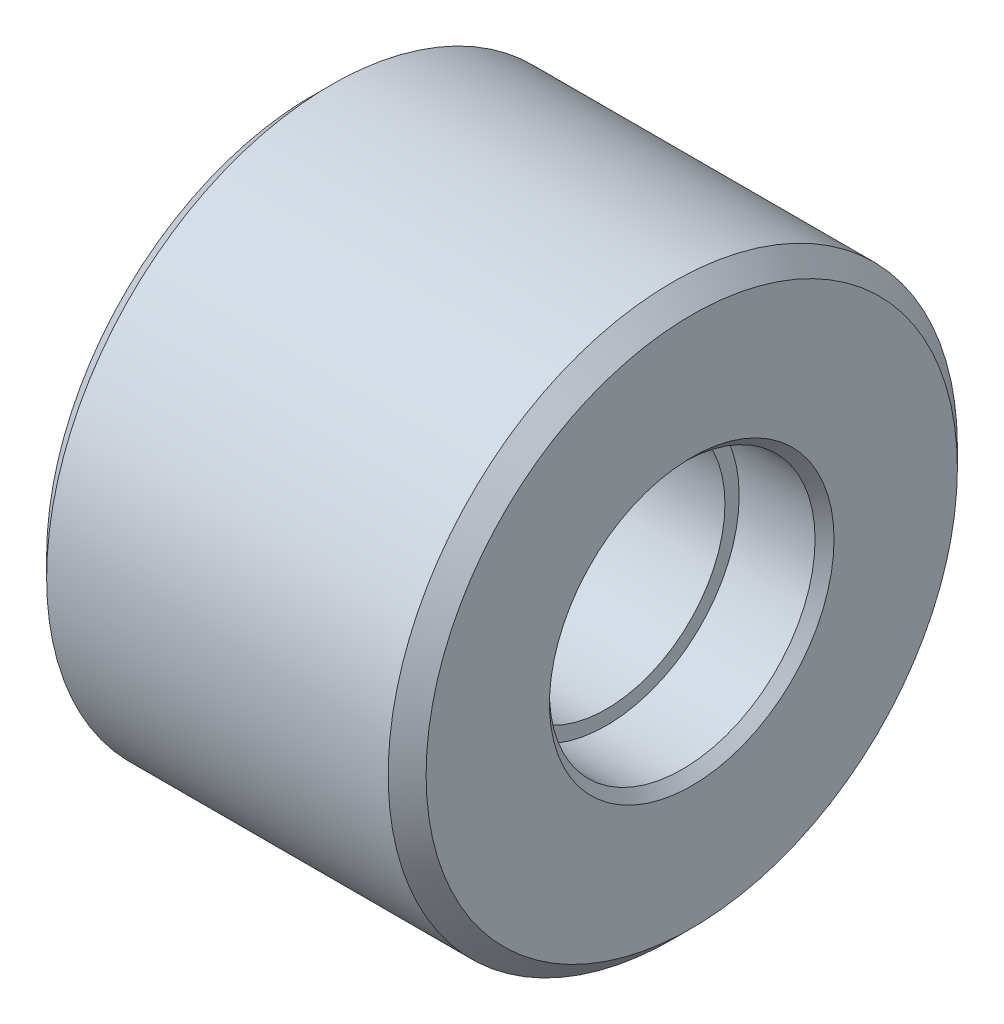
SolidWorks part; units mm, degrees
material "Nylon 101"
ref_plane "Спереди" through (0, 0, 0) normal (0, 0, 1) x (1, 0, 0)
ref_plane "Сверху" through (0, 0, 0) normal (0, 1, 0) x (1, 0, 0)
ref_plane "Справа" through (0, 0, 0) normal (1, 0, 0) x (0, 0, -1)
sketch "Эскиз1" plane through (0, 0, 0) normal (0, 0, 1) x (1, 0, 0)
  line L0 (0, 0) -> (-50000, 0) construction
  line L9 (0, 0) -> (0, 50000) construction
  line L10 (-20, 30) -> (20, 30)
  line L11 (20, 30) -> (20, 14)
  line L12 (20, 14) -> (11, 14)
  line L13 (-20, 14) -> (-20, 30)
  line L14 (-11, 14) -> (-11, 12.5)
  line L15 (-11, 12.5) -> (11, 12.5)
  line L16 (11, 12.5) -> (11, 14)
  line L17 (-11, 14) -> (-20, 14)
  dimension "D1" = 28
  dimension "D2" = 60
  dimension "D3" = 40
  dimension "D4" = 25
  dimension "D5" = 9
revolve "Повернуть1" add sketch "Эскиз1" angle 360 about L0
chamfer "Фаска1" distance 2 angle 45 2 edges at (-20, 0, -30) (20, 0, -30)
chamfer "Фаска2" distance 1 angle 45 2 edges at (20, 0, -14) (-20, 0, -14)
